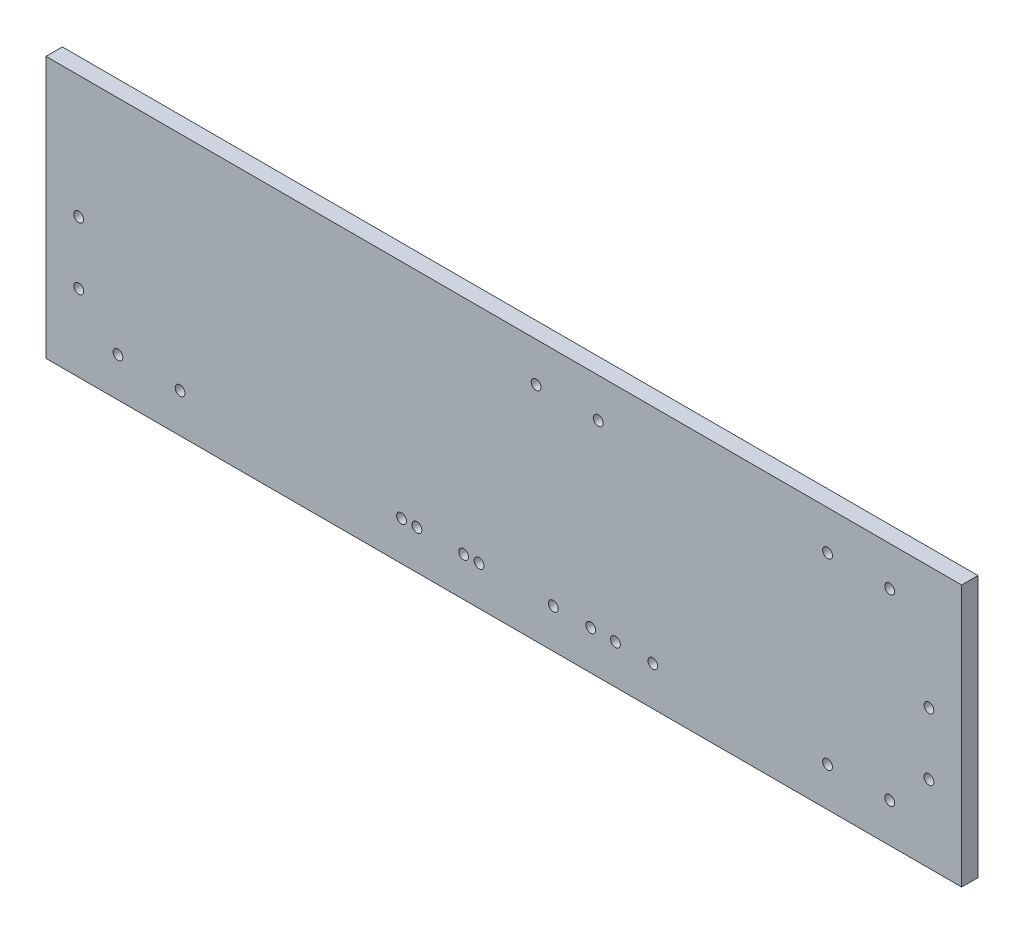
SolidWorks part; units mm, degrees
ref_plane "Front Plane" through (0, 0, 0) normal (0, 0, 1) x (1, 0, 0)
ref_plane "Top Plane" through (0, 0, 0) normal (0, 1, 0) x (1, 0, 0)
ref_plane "Right Plane" through (0, 0, 0) normal (1, 0, 0) x (0, 0, -1)
sketch "Sketch1" plane through (0, 0, 0) normal (0, 0, 1) x (1, 0, 0)
  line L1 (0, 0) -> (355.6, 0)
  line L2 (0, 0) -> (0, 101.6)
  line L3 (0, 101.6) -> (355.6, 101.6)
  line L4 (355.6, 0) -> (355.6, 101.6)
  dimension "D1" = 101.6
  dimension "D2" = 355.6
extrude "Boss-Extrude1" add sketch "Sketch1" along normal blind 6.35
sketch "Sketch2" plane through (0, 0, 6.35) normal (0, 0, 1) x (1, 0, 0)
  line L0 (27.94, 15.24) -> (27.94, 0) construction
  line L1 (27.94, 15.24) -> (0, 15.24) construction
  line L2 (0, 101.6) -> (0, 0) construction
  line L5 (52.07, 15.24) -> (27.94, 15.24) construction
  line L6 (0, 0) -> (355.6, 0) construction
  circle A0 centre (27.94, 15.24) radius 1.905
  circle A1 centre (52.07, 15.24) radius 1.905
  point P13 (1219.2, 76.2)
  dimension "D2" = 3.81
  dimension "D1" = 3.81
  dimension "D4" = 27.94
  dimension "D5" = 15.24
  dimension "D3" = 24.13
extrude "Cut-Extrude1" cut sketch "Sketch2" against normal up to surface (6.35 mm away) contours A1 | A0 up to face at (177.8, 50.8, 0)
sketch "Sketch3" plane through (0, 0, 6.35) normal (0, 0, 1) x (1, 0, 0)
  line L0 (12.7, 41.91) -> (0, 41.91) construction
  line L1 (355.6, 101.6) -> (0, 101.6) construction
  line L2 (12.7, 29.845) -> (12.7, 53.975) construction
  line L3 (0, 101.6) -> (0, 0) construction
  line L4 (6.35, 41.91) -> (6.35, 0) construction
  line L5 (177.8, 101.6) -> (177.8, 0) construction
  line L6 (0, 0) -> (355.6, 0) construction
  circle A0 centre (12.7, 29.845) radius 1.905
  circle A1 centre (12.7, 53.975) radius 1.905
  circle A2 centre (342.9, 29.845) radius 1.905
  circle A3 centre (342.9, 53.975) radius 1.905
  point P15 (177.8, 101.6)
  point P28 (12.7, 41.91)
  dimension "D2" = 3.81
  dimension "D1" = 3.81
  dimension "D3" = 24.13
  dimension "D4" = 12.7
  dimension "D5" = 41.91
extrude "Cut-Extrude2" cut sketch "Sketch3" against normal up to surface (6.35 mm away) up to face at (26.035, 15.24, 0)
pattern_linear "LPattern-bs-right" count 2 spacing 110.127 along (1, 0, 0) of "Cut-Extrude1"
pattern_linear "LPattern-ua-angled" count 2 spacing 116.1047 along (1, 0, 0) of "Cut-Extrude1"
sketch "Sketch4" plane through (0, 0, 6.35) normal (0, 0, 1) x (1, 0, 0)
  line L0 (327.66, 15.24) -> (355.6, 15.24) construction
  line L2 (355.6, 0) -> (355.6, 101.6) construction
  line L3 (327.66, 15.24) -> (327.66, 0) construction
  line L4 (0, 0) -> (355.6, 0) construction
  line L5 (327.66, 15.24) -> (303.53, 15.24) construction
  circle A0 centre (327.66, 15.24) radius 1.905
  circle A1 centre (303.53, 15.24) radius 1.905
  dimension "D4" = 3.81
  dimension "D5" = 3.81
  dimension "D1" = 27.94
  dimension "D2" = 24.13
  dimension "D3" = 15.24
extrude "Cut-Extrude4" cut sketch "Sketch4" against normal up to surface (6.35 mm away) up to face at (142.1397, 15.24, 0)
pattern_linear "LPattern-ua-left" count 2 spacing 91.9843 along (-1, 0, 0) of "Cut-Extrude4"
pattern_linear "LPattern4-ua-right" count 2 spacing 106.4986 along (-1, 0, 0) of "Cut-Extrude4"
sketch "Sketch5" plane through (0, 0, 6.35) normal (0, 0, 1) x (1, 0, 0)
  line L0 (327.66, 86.36) -> (355.6, 86.36) construction
  line L1 (355.6, 0) -> (355.6, 101.6) construction
  line L2 (303.53, 86.36) -> (327.66, 86.36) construction
  line L3 (327.66, 86.36) -> (327.66, 101.6) construction
  line L4 (355.6, 101.6) -> (0, 101.6) construction
  circle A0 centre (327.66, 86.36) radius 1.905
  circle A1 centre (303.53, 86.36) radius 1.905
  dimension "D4" = 3.81
  dimension "D5" = 3.81
  dimension "D3" = 15.24
  dimension "D1" = 24.13
  dimension "D2" = 27.94
extrude "Cut-Extrude5" cut sketch "Sketch5" against normal up to surface (6.35 mm away) up to face at (195.1264, 15.24, 0)
pattern_linear "LPattern5" count 2 spacing 113.1994 along (-1, 0, 0) of "Cut-Extrude5"
equation "\"vertical-component-width\"= 14in"
equation "\"vertical-component-height\"= 4in"
equation "\"material-thickness\"= .25in"
equation "\"D1@Sketch1\"=\"vertical-component-height\""
equation "\"D2@Sketch1\"=\"vertical-component-width\""
equation "\"D1@Boss-Extrude1\"=\"material-thickness\""
equation "\"mounting-hole-diameter\"= .15in"
equation "\"mounting-hole-pair-left-hole-center-to-mount-edge-left\"= 1.1in"
equation "\"mounting-hole-center-to-mount-edge-bottom\"= .6in"
equation "\"mounting-hole-pair-distance-between-hole-centers\"= .95in"
equation "\"num-mounting-hole-pairs\"= 2"
equation "\"D2@Sketch2\"=\"mounting-hole-diameter\""
equation "\"D1@Sketch2\"=\"mounting-hole-diameter\""
equation "\"edge-mounting-hole-center-to-mount-edge-left\"= 0.5in"
equation "\"edge-mounting-hole-pair-offset-from-mount-vertical-center\"= 0.15in"
equation "\"ua-right-distance-between-left-mounting-holes\"= 4.19286in"
equation "\"bs-angled-distance-between-left-mounting-holes\"= 4.45667in"
equation "\"ua-left-distance-between-left-mounting-holes\"= 3.62143in"
equation "\"ua-angled-distance-between-left-mounting-holes\"= 4.57105in"
equation "\"bs-right-distance-between-left-mounting-holes\"= 4.33571in"
equation "\"D1@Sketch3\"=\"mounting-hole-diameter\""
equation "\"D2@Sketch3\"=\"mounting-hole-diameter\""
equation "\"D3@LPattern-bs-right\"=\"bs-right-distance-between-left-mounting-holes\""
equation "\"D1@LPattern-bs-right\"=\"num-mounting-hole-pairs\""
equation "\"D3@LPattern-ua-angled\" = \"ua-angled-distance-between-left-mounting-holes\""
equation "\"D1@LPattern-ua-angled\" = \"num-mounting-hole-pairs\""
equation "\"D4@Sketch2\"=\"mounting-hole-pair-left-hole-center-to-mount-edge-left\""
equation "\"D5@Sketch2\"=\"mounting-hole-center-to-mount-edge-bottom\""
equation "\"D3@Sketch2\"=\"mounting-hole-pair-distance-between-hole-centers\""
equation "\"D3@Sketch3\"=\"mounting-hole-pair-distance-between-hole-centers\""
equation "\"D1@Sketch4\"=\"mounting-hole-pair-left-hole-center-to-mount-edge-left\""
equation "\"D2@Sketch4\"=\"mounting-hole-pair-distance-between-hole-centers\""
equation "\"D3@Sketch4\"=\"mounting-hole-center-to-mount-edge-bottom\""
equation "\"D3@LPattern-ua-left\"=\"ua-left-distance-between-left-mounting-holes\""
equation "\"D1@LPattern-ua-left\"=\"num-mounting-hole-pairs\""
equation "\"D3@LPattern4-ua-right\"=\"ua-right-distance-between-left-mounting-holes\""
equation "\"D1@Sketch5\"=\"mounting-hole-pair-distance-between-hole-centers\""
equation "\"D2@Sketch5\"=\"mounting-hole-pair-left-hole-center-to-mount-edge-left\""
equation "\"D3@Sketch5\"=\"mounting-hole-center-to-mount-edge-bottom\""
equation "\"D4@Sketch5\"=\"mounting-hole-diameter\""
equation "\"D5@Sketch5\"=\"mounting-hole-diameter\""
equation "\"D4@Sketch4\"=\"mounting-hole-diameter\""
equation "\"D5@Sketch4\"=\"mounting-hole-diameter\""
equation "\"D3@LPattern5\"=\"bs-angled-distance-between-left-mounting-holes\""
equation "\"D1@LPattern5\"=\"num-mounting-hole-pairs\""
equation "\"edge-mounting-hole-pair-center-to-mount-edge-bottom\"= 1.65in"
equation "\"D4@Sketch3\"=\"edge-mounting-hole-center-to-mount-edge-left\""
equation "\"D5@Sketch3\"=\"edge-mounting-hole-pair-center-to-mount-edge-bottom\""
